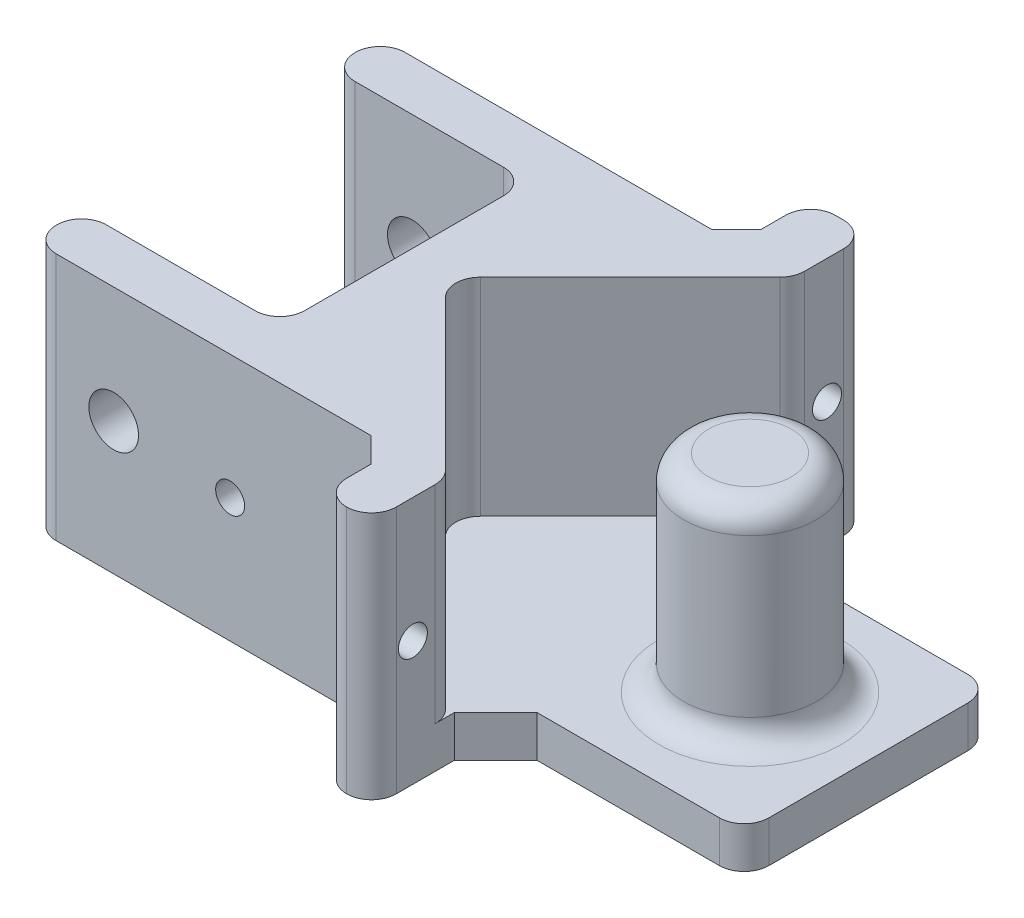
SolidWorks part; units mm, degrees
ref_plane "Front Plane" through (0, 0, 0) normal (0, 0, 1) x (1, 0, 0)
ref_plane "Top Plane" through (0, 0, 0) normal (0, 1, 0) x (1, 0, 0)
ref_plane "Right Plane" through (0, 0, 0) normal (1, 0, 0) x (0, 0, -1)
sketch "Sketch1" plane through (0, 0, 0) normal (0, 1, 0) x (1, 0, 0)
  line L0 (-65, 21.0624) -> (-65, -21.0624)
  line L1 (0, -36.0624) -> (36.0624, 0) construction
  line L2 (0, -36.0624) -> (-36.0624, 0) construction
  line L3 (-36.0624, 0) -> (0, 36.0624) construction
  line L4 (36.0624, 0) -> (0, 36.0624) construction
  line L5 (0, -36.0624) -> (0, 36.0624) construction
  line L6 (-36.0624, 0) -> (36.0624, 0) construction
  line L7 (-21.0058, -30) -> (-15, -30)
  line L8 (-15, -30) -> (-15, -21.0624)
  line L9 (-15, -21.0624) -> (-36.0624, 0)
  line L10 (-36.0624, 0) -> (-15, 21.0624)
  line L11 (-15, 21.0624) -> (-15, 30)
  line L12 (-15, 30) -> (-22, 30)
  line L13 (-21.0058, -21.0624) -> (-65, -21.0624)
  line L14 (-21.0058, -21.0624) -> (-21.0058, -30)
  line L15 (-65, 21.0624) -> (-22, 21.0624)
  line L16 (-22, 21.0624) -> (-22, 30)
  circle A0 centre (0.7071, 0) radius 8
  point P0 (0, 0)
  dimension "D7" = 16
  dimension "D8" = 26
  dimension "D9" = 26
  dimension "D1" = 51
  dimension "D2" = 51
  dimension "D3" = 30
  dimension "D4" = 65
  dimension "D5" = 7
  dimension "D6" = 30
extrude "Boss-Extrude1" add sketch "Sketch1" along normal blind 30
sketch "Sketch2" plane through (0, 30, 0) normal (0, 1, 0) x (1, 0, 0)
  line L1 (-71.0624, 15) -> (-41.0624, 15)
  line L2 (-71.0624, 15) -> (-71.0624, -15)
  line L3 (-71.0624, -15) -> (-41.0624, -15)
  line L4 (-41.0624, 15) -> (-41.0624, -15)
  line L5 (-71.0624, 15) -> (-41.0624, -15) construction
  line L6 (-71.0624, -15) -> (-41.0624, 15) construction
  point P0 (-56.0624, 0)
  dimension "D1" = 30
  dimension "D2" = 30
  dimension "D3" = 20
extrude "Cut-Extrude1" cut sketch "Sketch2" against normal blind 30
chamfer "Chamfer1" distance 3 angle 45 2 edges at (-21.0058, 15, 21.0624) (-22, 15, -21.0624)
fillet "Fillet1" radius 3 5 edges at (-36.0624, 15, 0) (-41.0624, 15, 15) (-41.0624, 15, -15) (-15, 15, 21.0624) (-15, 15, -21.0624)
fillet "Fillet2" radius 3 8 edges at (-65, 15, 15) (-65, 15, -21.0624) (-65, 15, -15) (-65, 15, 21.0624) (-21.0058, 15, 30) (-15, 15, 30) (-22, 15, -30) (-15, 15, -30)
sketch "Sketch3" plane through (-22, 0, 0) normal (-1, 0, 0) x (0, 0, 1)
  circle A0 centre (-25, 15) radius 1.75
  circle A1 centre (25, 15) radius 1.75
  dimension "D1" = 3.5
  dimension "D2" = 3.5
  dimension "D3" = 15
  dimension "D4" = 25
  dimension "D5" = 25
extrude "Cut-Extrude2" cut sketch "Sketch3" against normal blind 30 and the other way blind 30
sketch "Sketch4" plane through (0, 0, -15) normal (0, 0, 1) x (1, 0, 0)
  line L0 (-41.0624, 30) -> (-41.0624, 0) construction
  circle A0 centre (-55.0624, 15.9838) radius 3
  dimension "D1" = 6
  dimension "D2" = 14
extrude "Cut-Extrude3" cut sketch "Sketch4" against normal blind 30 and the other way blind 50
sketch "Sketch5" plane through (0, 0, -21.0624) normal (0, 0, -1) x (-1, 0, 0)
  circle A0 centre (41, 15) radius 1.75
  dimension "D1" = 3.5
  dimension "D2" = 15
  dimension "D3" = 41
extrude "Cut-Extrude4" cut sketch "Sketch5" against normal through all both and the other way through all
sketch "Sketch6" plane through (0, 0, 0) normal (0, 1, 0) x (1, 0, 0)
  line L0 (-15, 15) -> (15, 15)
  line L2 (15, 15) -> (15, -15)
  line L3 (15, -15) -> (-15, -15)
  line L4 (-15, 23.9288) -> (-37.2978, 2.8035)
  line L7 (-15, 23.9288) -> (-15, 15)
  line L8 (-15, 22.3051) -> (-15, 27) construction
  line L9 (-15, -24.6525) -> (-15, -15)
  line L10 (-15, -27) -> (-15, -22.3051) construction
  line L11 (-37.2978, 2.8035) -> (-37.2978, -1.4157)
  line L12 (-37.2978, -1.4157) -> (-15, -24.6525)
  dimension "D1" = 15
  dimension "D2" = 15
  dimension "D3" = 15
extrude "Boss-Extrude2" add sketch "Sketch6" along normal blind 5
fillet "Fillet3" radius 3 1 edges at (0.7071, 30, 8)
fillet "Fillet4" radius 3 2 edges at (15, 2.5, -15) (15, 2.5, 15)
fillet "Fillet5" radius 3 1 edges at (0.7071, 5, -8)
chamfer "Chamfer5" distance 5 angle 45 2 edges at (-15, 2.5, 15) (-15, 2.5, -15)
